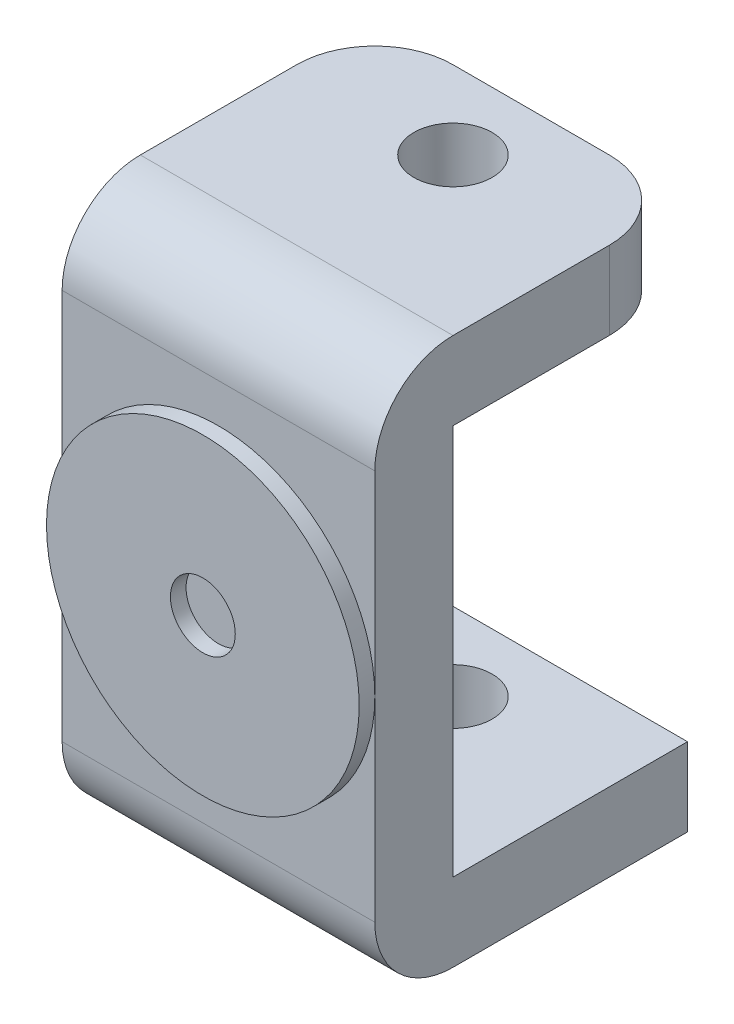
SolidWorks part; units mm, degrees
ref_plane "Front Plane" through (0, 0, 0) normal (0, 0, 1) x (1, 0, 0)
ref_plane "Top Plane" through (0, 0, 0) normal (0, 1, 0) x (1, 0, 0)
ref_plane "Right Plane" through (0, 0, 0) normal (1, 0, 0) x (0, 0, -1)
sketch "Sketch1" plane through (0, 0, 0) normal (0, 0, 1) x (1, 0, 0)
  line L1 (-2, 2.5) -> (2, 2.5)
  line L2 (-2, 2.5) -> (-2, -2.5)
  line L3 (-2, -2.5) -> (2, -2.5)
  line L4 (2, 2.5) -> (2, -2.5)
  line L5 (-2, 2.5) -> (2, -2.5) construction
  line L6 (-2, -2.5) -> (2, 2.5) construction
  point P0 (0, 0)
  dimension "D1" = 4
  dimension "D2" = 5
extrude "Boss-Extrude1" add sketch "Sketch1" along normal blind 1
sketch "Sketch2" plane through (0, 0, 0) normal (1, 0, 0) x (0, 0, -1)
  line L1 (-1, 2.5) -> (3, 2.5)
  line L2 (-1, 2.5) -> (-1, 3.5)
  line L3 (-1, 3.5) -> (3, 3.5)
  line L4 (3, 2.5) -> (3, 3.5)
  line L5 (-1, -2.5) -> (3, -2.5)
  line L6 (-1, -2.5) -> (-1, -3.5)
  line L7 (-1, -3.5) -> (3, -3.5)
  line L8 (3, -2.5) -> (3, -3.5)
  dimension "D1" = 1
  dimension "D2" = 1
  dimension "D3" = 4
  dimension "D4" = 4
extrude "Boss-Extrude2" add sketch "Sketch2" along normal mid plane 4
fillet "Fillet1" radius 1 4 edges at (0, -3.5, 1) (-2, 3, -3) (0, 3.5, 1) (2, 3, -3)
sketch "Sketch3" plane through (0, 0, 1) normal (0, 0, 1) x (1, 0, 0)
  circle A0 centre (0, 0) radius 2
  circle A1 centre (0, 0) radius 0.415
  dimension "D1" = 0.83
  dimension "D2" = 4
extrude "Boss-Extrude3" add sketch "Sketch3" along normal blind 0.2
sketch "Sketch4" plane through (0, -3.5, 0) normal (0, -1, 0) x (1, 0, 0)
  line L0 (0, -3) -> (0, -2)
  line L1 (2, -3) -> (-2, -3) construction
  circle A0 centre (0, -2) radius 0.5
  dimension "D2" = 1
  dimension "D1" = 1
extrude "Cut-Extrude1" cut sketch "Sketch4" against normal through all
